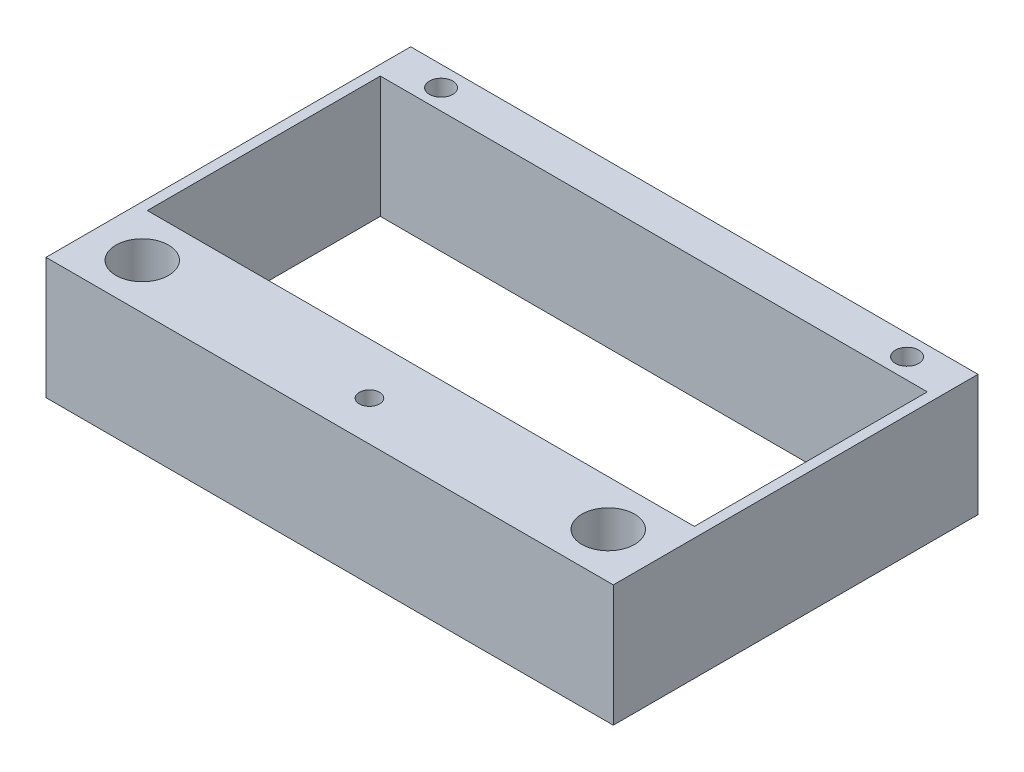
SolidWorks part; units mm, degrees
ref_plane "前视基准面" through (0, 0, 0) normal (0, 0, 1) x (1, 0, 0)
ref_plane "上视基准面" through (0, 0, 0) normal (0, 1, 0) x (1, 0, 0)
ref_plane "右视基准面" through (0, 0, 0) normal (1, 0, 0) x (0, 0, -1)
other "Configuration Table"
sketch "草图2" plane through (0, 0, 0) normal (0, 1, 0) x (1, 0, 0)
  line L0 (-10.7257, 9.9292) -> (45.2743, 9.9292)
  line L1 (45.2743, 9.9292) -> (45.2743, -22.0708)
  line L2 (45.2743, -22.0708) -> (-10.7257, -22.0708)
  line L3 (-10.7257, -22.0708) -> (-10.7257, -7.0708)
  line L5 (-9.7257, -7.0708) -> (-9.7257, -14.0708)
  line L6 (-9.7257, -14.0708) -> (44.2743, -14.0708)
  line L7 (44.2743, -14.0708) -> (44.2743, 8.9292)
  line L8 (44.2743, 8.9292) -> (-9.7257, 8.9292)
  line L9 (-9.7257, 8.9292) -> (-9.7257, 0.9292)
  line L11 (-10.7257, 1.9292) -> (-10.7257, 9.9292)
  line L12 (-10.7257, 1.9292) -> (-10.7257, -7.0708)
  line L13 (-9.7257, -7.0708) -> (-9.7257, 0.9292)
  dimension "D1" = 1
  dimension "D2" = 56
  dimension "D3" = 32
  dimension "D4" = 8
  dimension "D5" = 1
  dimension "D7" = 54
extrude "凸台-拉伸1" add sketch "草图2" along normal blind 12
ref_plane "基准面1" through (0, 12, 0) normal (0, 1, 0) x (1, 0, 0)
sketch "草图4" plane through (0, 0, 0) normal (0, 1, 0) x (1, 0, 0)
  line L1 (-10.7257, 9.9292) -> (45.2743, 9.9292)
  line L2 (-10.7257, 9.9292) -> (-10.7257, 12.9292)
  line L3 (-10.7257, 12.9292) -> (45.2743, 12.9292)
  line L4 (45.2743, 9.9292) -> (45.2743, 12.9292)
  line L5 (-10.7257, -22.0708) -> (45.2743, -22.0708)
  line L6 (-10.7257, -22.0708) -> (-10.7257, -23.0708)
  line L7 (-10.7257, -23.0708) -> (45.2743, -23.0708)
  line L8 (45.2743, -22.0708) -> (45.2743, -23.0708)
  dimension "D1" = 3
  dimension "D2" = 1
extrude "凸台-拉伸2" add sketch "草图4" along normal blind 12
sketch "草图5" plane through (0, 12, 0) normal (0, 1, 0) x (1, 0, 0)
  line L0 (45.2743, 12.9292) -> (-10.7257, 12.9292) construction
  line L1 (-10.7257, 12.9292) -> (-10.7257, -23.0708) construction
  line L2 (45.2743, -23.0708) -> (45.2743, 12.9292) construction
  line L3 (-10.7257, -23.0708) -> (45.2743, -23.0708) construction
  line L4 (23.666, -14.0708) -> (23.666, -23.0708) construction
  line L5 (-9.7257, -14.0708) -> (44.2743, -14.0708) construction
  line L6 (23.666, -18.5708) -> (28.7156, -18.5708) construction
  circle A0 centre (-5.7257, 10.9292) radius 1.15
  circle A1 centre (40.2743, 10.9292) radius 1.15
  circle A4 centre (-5.7257, -18.5708) radius 2.6
  circle A5 centre (40.2743, -18.5708) radius 2.6
  dimension "D1" = 2
  dimension "D2" = 5
  dimension "D3" = 5
  dimension "D4" = 2
extrude "切除-拉伸2" cut sketch "草图5" against normal through all
sketch "草图7" plane through (0, 12, 0) normal (0, 1, 0) x (1, 0, 0)
  line L0 (-10.7257, -19.143) -> (45.2743, -19.143) construction
  line L1 (-10.7257, 12.9292) -> (-10.7257, -23.0708) construction
  line L2 (45.2743, -23.0708) -> (45.2743, 12.9292) construction
  circle A0 centre (17.2743, -19.143) radius 1
extrude "切除-拉伸3" cut sketch "草图7" against normal blind 10
